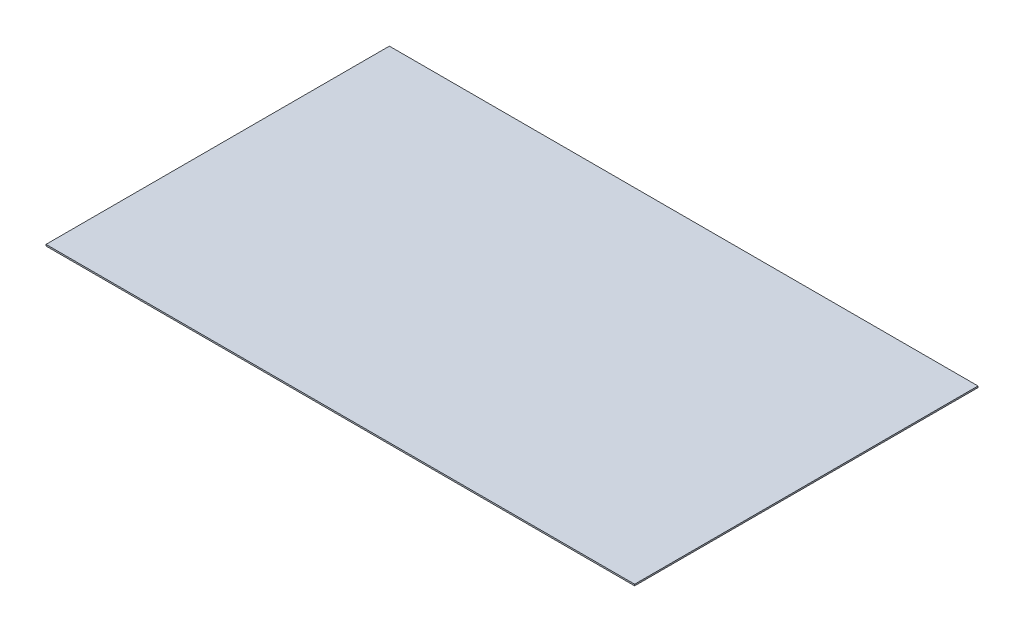
SolidWorks part; units mm, degrees
ref_plane "Front Plane" through (0, 0, 0) normal (0, 0, 1) x (1, 0, 0)
ref_plane "Top Plane" through (0, 0, 0) normal (0, 1, 0) x (1, 0, 0)
ref_plane "Right Plane" through (0, 0, 0) normal (1, 0, 0) x (0, 0, -1)
sketch "Sketch1" plane through (0, 0, 0) normal (0, 1, 0) x (1, 0, 0)
  line L1 (600, -350) -> (-600, -350)
  line L2 (600, -350) -> (600, 350)
  line L3 (600, 350) -> (-600, 350)
  line L4 (-600, -350) -> (-600, 350)
  line L5 (600, -350) -> (-600, 350) construction
  line L6 (600, 350) -> (-600, -350) construction
  point P0 (0, 0)
extrude "Boss-Extrude1" add sketch "Sketch1" along normal blind 3
